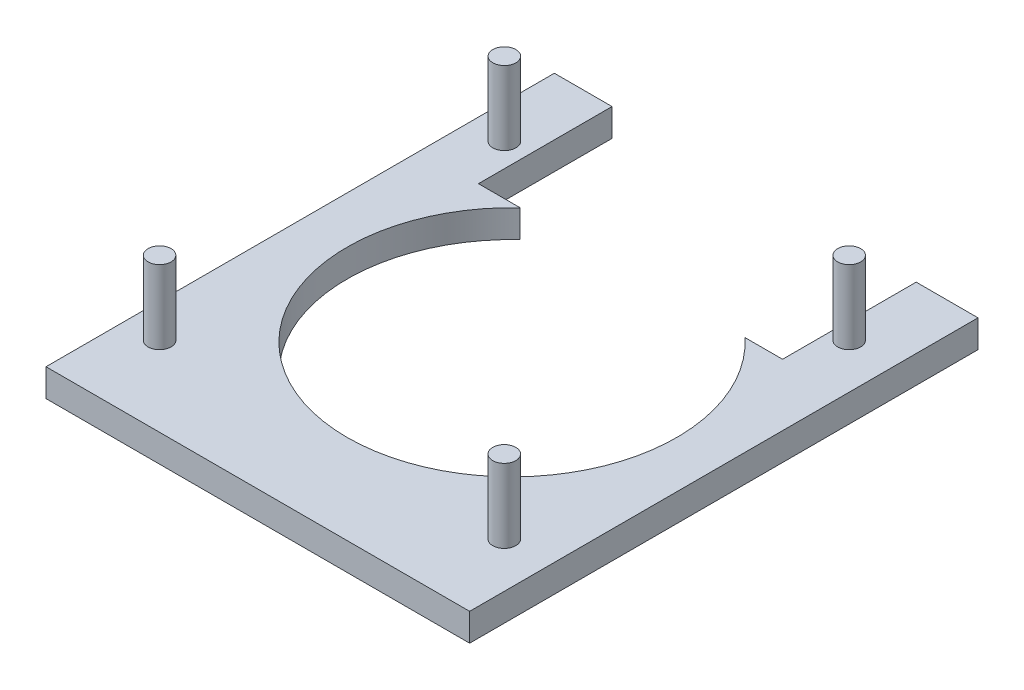
SolidWorks part; units mm, degrees
ref_plane "Front Plane" through (0, 0, 0) normal (0, 0, 1) x (1, 0, 0)
ref_plane "Top Plane" through (0, 0, 0) normal (0, 1, 0) x (1, 0, 0)
ref_plane "Right Plane" through (0, 0, 0) normal (1, 0, 0) x (0, 0, -1)
sketch "Sketch1" plane through (0, 0, 0) normal (0, 1, 0) x (1, 0, 0)
  line L1 (-23, -27.6) -> (23, -27.6)
  line L2 (-23, -27.6) -> (-23, 27.6)
  line L3 (-23, 27.6) -> (23, 27.6)
  line L4 (23, -27.6) -> (23, 27.6)
  line L5 (-23, -27.6) -> (23, 27.6) construction
  line L6 (-23, 27.6) -> (23, -27.6) construction
  point P0 (0, 0)
extrude "Boss-Extrude1" add sketch "Sketch1" along normal blind 3
sketch "Sketch2" plane through (0, 3, 0) normal (0, 1, 0) x (1, 0, 0)
  line L0 (-19.3179, 18.49) -> (18.1221, 18.49)
  line L1 (-19.3179, 18.49) -> (-19.3179, -18.95)
  line L2 (-19.3179, -18.95) -> (18.1221, -18.95)
  line L3 (18.1221, 18.49) -> (18.1221, -18.95)
  circle A0 centre (-19.3179, 18.49) radius 1.25
  circle A1 centre (18.1221, 18.49) radius 1.25
  circle A2 centre (-19.3179, -18.95) radius 1.25
  circle A3 centre (18.1221, -18.95) radius 1.25
sketch "Sketch3" plane through (0, 3, 0) normal (0, 1, 0) x (1, 0, 0)
  circle A0 centre (0, 0) radius 17.9
sketch "Sketch4" plane through (0, 3, 0) normal (0, 1, 0) x (1, 0, 0)
  line L1 (-16.7358, 33.9203) -> (16.2875, 33.9203)
  line L2 (-16.7358, 33.9203) -> (-16.7358, 13.0921)
  line L3 (-16.7358, 13.0921) -> (16.2875, 13.0921)
  line L4 (16.2875, 33.9203) -> (16.2875, 13.0921)
  line L5 (-16.7358, 33.9203) -> (16.2875, 13.0921) construction
  line L6 (-16.7358, 13.0921) -> (16.2875, 33.9203) construction
  point P0 (-0.2241, 23.5062)
extrude "Cut-Extrude1" cut sketch "Sketch4" against normal blind 8 contours L2 L1 L4 L3
sketch "Sketch5" plane through (0, 3, 0) normal (0, 1, 0) x (1, 0, 0)
  circle A0 centre (-19.3179, 18.49) radius 1.25
  circle A1 centre (18.1221, 18.49) radius 1.25
  circle A2 centre (-19.3179, -18.95) radius 1.25
  circle A3 centre (18.0841, -18.9245) radius 1.25
extrude "Cut-Extrude2" cut sketch "Sketch3" against normal blind 8
extrude "Boss-Extrude2" add sketch "Sketch5" along normal blind 8
